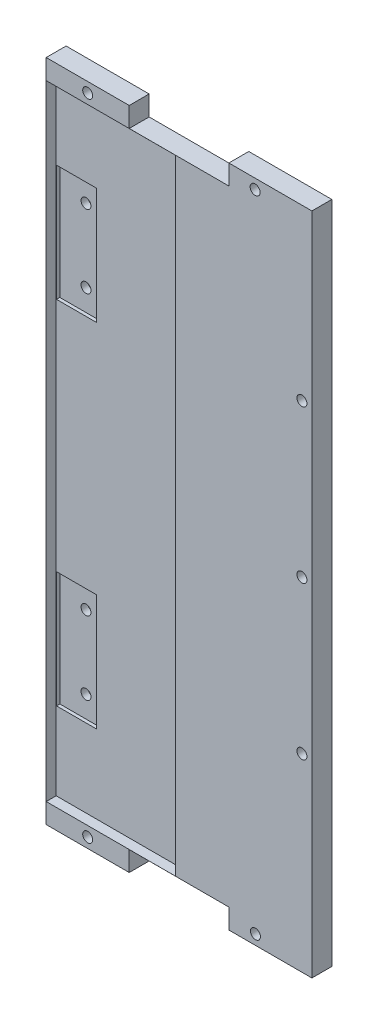
SolidWorks part; units mm, degrees
ref_plane "Plan de face" through (0, 0, 0) normal (0, 0, 1) x (1, 0, 0)
ref_plane "Plan de dessus" through (0, 0, 0) normal (0, 1, 0) x (1, 0, 0)
ref_plane "Plan de droite" through (0, 0, 0) normal (1, 0, 0) x (0, 0, -1)
sketch "Esquisse1" plane through (0, 0, 0) normal (0, 0, 1) x (1, 0, 0)
  line L1 (40, -100) -> (-40, -100)
  line L2 (40, -100) -> (40, 100)
  line L3 (40, 100) -> (-40, 100)
  line L4 (-40, -100) -> (-40, 100)
  line L5 (40, -100) -> (-40, 100) construction
  line L6 (40, 100) -> (-40, -100) construction
  point P0 (0, 0)
extrude "Boss.-Extru.1" add sketch "Esquisse1" along normal blind 6
sketch "Esquisse4" plane through (0, 0, 6) normal (0, 0, 1) x (1, 0, 0)
  line L0 (40, 100) -> (-40, 100) construction
  line L1 (-40, -100) -> (40, -100) construction
  line L2 (-0.99, 93.99) -> (-39.99, 93.99)
  line L3 (-0.99, 93.99) -> (-0.99, -93.99)
  line L4 (-0.99, -93.99) -> (-39.99, -93.99)
  line L5 (-40, 100) -> (-40, -100) construction
  line L6 (-39.99, 93.99) -> (-39.99, -93.99)
  dimension "D1" = 6.01
  dimension "D2" = 6.01
  dimension "D3" = 39
  dimension "D4" = 0.01
extrude "Enlèv. mat.-Extru.3" cut sketch "Esquisse4" against normal blind 3
sketch "Esquisse5" plane through (0, 0, 6) normal (0, 0, 1) x (1, 0, 0)
  line L0 (40, 100) -> (-40, 100) construction
  line L1 (-15, 100) -> (15, 100)
  line L2 (-15, 100) -> (-15, 94)
  line L3 (-15, 94) -> (15, 94)
  line L4 (15, 100) -> (15, 94)
  line L5 (-40, -100) -> (40, -100) construction
  line L6 (-15, -100) -> (15, -100)
  line L7 (-15, -100) -> (-15, -94)
  line L8 (-15, -94) -> (15, -94)
  line L9 (15, -100) -> (15, -94)
  line L10 (-40, 100) -> (-40, -100) construction
  dimension "D1" = 25
  dimension "D2" = 30
  dimension "D3" = 6
  dimension "D4" = 6
  dimension "D5" = 25
  dimension "D6" = 30
extrude "Enlèv. mat.-Extru.4" cut sketch "Esquisse5" against normal blind 10
sketch "Esquisse6" plane through (0, 0, 0) normal (0, 0, -1) x (-1, 0, 0)
  line L0 (40, -100) -> (15, -100) construction
  line L1 (15, -94) -> (15, -100) construction
  line L2 (15, 100) -> (40, 100) construction
  line L3 (15, 100) -> (15, 94) construction
  line L4 (-15, -100) -> (-15, -94) construction
  circle A0 centre (27.5, -97) radius 2.995
  circle A1 centre (-23, -97) radius 2.995
  circle A2 centre (27.5, 97) radius 2.995
  circle A3 centre (-23, 97) radius 2.995
  point P12 (15, 97)
  dimension "D1" = 5.99
  dimension "D4" = 5.99
  dimension "D5" = 5.99
  dimension "D9" = 5.99
  dimension "D2" = 3
  dimension "D3" = 12.5
  dimension "D6" = 3
  dimension "D7" = 12.5
  dimension "D8" = 8
extrude "Enlèv. mat.-Extru.5" cut sketch "Esquisse6" against normal blind 3
sketch "Esquisse7" plane through (0, 0, 0) normal (0, 0, -1) x (-1, 0, 0)
  circle A0 centre (27.5, 97) radius 1.5
  circle A1 centre (-22.9096, 97) radius 1.5
  circle A2 centre (27.5, -97) radius 1.5
  circle A3 centre (-23, -97) radius 1.5
extrude "Enlèv. mat.-Extru.6" cut sketch "Esquisse7" against normal blind 13
sketch "Esquisse8" plane through (0, 0, 3) normal (0, 0, 1) x (1, 0, 0)
  line L2 (-15, 100) -> (-40, 100) construction
  line L3 (-40, -100) -> (-15, -100) construction
  circle A0 centre (-32.01, 64) radius 1.5
  circle A1 centre (-32.01, 42) radius 1.5
  circle A2 centre (-32.01, -42) radius 1.5
  circle A3 centre (-32.01, -64) radius 1.5
  dimension "D1" = 3
  dimension "D2" = 3
  dimension "D3" = 3
  dimension "D4" = 3
  dimension "D5" = 22
  dimension "D6" = 22
  dimension "D7" = 36
  dimension "D8" = 36
  dimension "D10" = 0
  dimension "D11" = 0
extrude "Enlèv. mat.-Extru.7" cut sketch "Esquisse8" against normal blind 10
sketch "Esquisse9" plane through (0, 0, 0) normal (0, 0, -1) x (-1, 0, 0)
  line L0 (-15, -94) -> (15, -94) construction
  line L2 (-40, -100) -> (-40, 100) construction
  circle A0 centre (-37, -43) radius 1.5
  circle A1 centre (-37, 3) radius 1.5
  circle A2 centre (-37, 49) radius 1.5
  dimension "D1" = 3
  dimension "D2" = 51
  dimension "D3" = 46
  dimension "D4" = 46
  dimension "D5" = 3
extrude "Enlèv. mat.-Extru.8" cut sketch "Esquisse9" against normal blind 10
sketch "Esquisse10" plane through (0, 0, 3) normal (0, 0, 1) x (1, 0, 0)
  line L2 (-39.9, 70.5) -> (-27.9, 70.5)
  line L3 (-39.9, 70.5) -> (-39.9, 35.5)
  line L4 (-39.9, 35.5) -> (-27.9, 35.5)
  line L5 (-27.9, 70.5) -> (-27.9, 35.5)
  line L6 (-27.9, -35.5) -> (-39.9, -35.5)
  line L7 (-27.9, -35.5) -> (-27.9, -70.5)
  line L8 (-27.9, -70.5) -> (-39.9, -70.5)
  line L9 (-39.9, -35.5) -> (-39.9, -70.5)
  dimension "D1" = 35
  dimension "D3" = 12
  dimension "D5" = 35
  dimension "D7" = 12
extrude "Enlèv. mat.-Extru.9" cut sketch "Esquisse10" against normal blind 1
